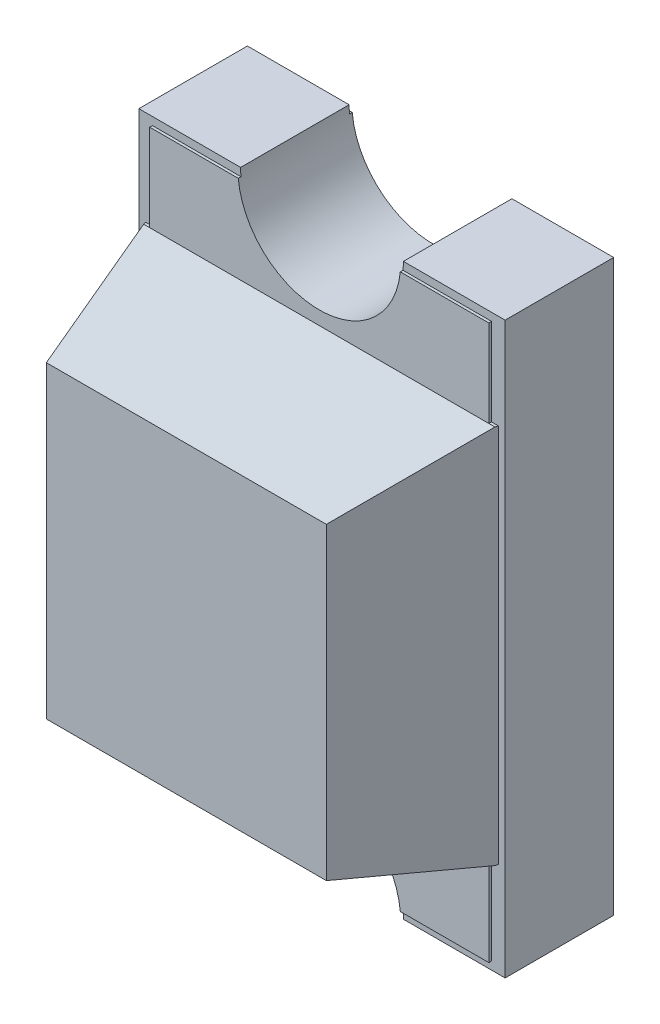
SolidWorks part; units mm, degrees
ref_plane "Front Plane" through (0, 0, 0) normal (0, 0, 1) x (1, 0, 0)
ref_plane "Top Plane" through (0, 0, 0) normal (0, 1, 0) x (1, 0, 0)
ref_plane "Right Plane" through (0, 0, 0) normal (1, 0, 0) x (0, 0, -1)
sketch "Sketch1" plane through (0, 0, 0) normal (0, 0, 1) x (1, 0, 0)
  line L0 (0, 0) -> (0, 842.0202) construction
  line L1 (0, 0) -> (842.0202, 0) construction
  line L3 (-0.675, 1.05) -> (0.675, 1.05)
  line L4 (-0.675, 1.05) -> (-0.675, -1.05)
  line L5 (-0.675, -1.05) -> (0.675, -1.05)
  line L6 (0.675, 1.05) -> (0.675, -1.05)
  dimension "D1" = 1.35
  dimension "D2" = 2.1
extrude "Boss-Extrude1" add sketch "Sketch1" along normal blind 0.4
sketch "Sketch3" plane through (0, 0, 0.4) normal (0, 0, 1) x (1, 0, 0)
  line L0 (0, 0) -> (0, 50000) construction
  line L1 (0, 0) -> (50000, 0) construction
  line L2 (-0.625, 1.0209) -> (0.625, 1.0209)
  line L3 (-0.625, 1.0209) -> (-0.625, 0.5209)
  line L4 (-0.625, 0.5209) -> (0.625, 0.5209)
  line L5 (0.625, 1.0209) -> (0.625, 0.5209)
  line L6 (-0.625, -1.0209) -> (-0.625, -0.5209)
  line L7 (-0.625, -0.5209) -> (0.625, -0.5209)
  line L8 (0.625, -1.0209) -> (0.625, -0.5209)
  line L9 (-0.625, -1.0209) -> (0.625, -1.0209)
  dimension "D1" = 1.25
  dimension "D2" = 0.5
extrude "Boss-Extrude2" add sketch "Sketch3" along normal blind 0.01 and the other way blind 0.41
sketch "Sketch2" plane through (0, 0, 0.4) normal (0, 0, 1) x (1, 0, 0)
  line L0 (0.675, 1.05) -> (-0.675, 1.05) construction
  line L1 (-0.675, -1.05) -> (0.675, -1.05) construction
  circle A0 centre (0, 1.05) radius 0.3
  circle A1 centre (0, -1.05) radius 0.3
  dimension "D1" = 0.6
extrude "Cut-Extrude1" cut sketch "Sketch2" against normal through all both and the other way through all
sketch "Sketch4" plane through (0, 0, 0.4) normal (0, 0, 1) x (1, 0, 0)
  line L0 (0, 0) -> (0, 50000) construction
  line L1 (0, 0) -> (50000, 0) construction
  line L3 (-0.65, 0.7) -> (0.65, 0.7)
  line L4 (-0.65, 0.7) -> (-0.65, -0.7)
  line L5 (-0.65, -0.7) -> (0.65, -0.7)
  line L6 (0.65, 0.7) -> (0.65, -0.7)
  dimension "D1" = 1.4
  dimension "D2" = 1.3
extrude "Boss-Extrude3" add sketch "Sketch4" along normal blind 0.5
sketch "Sketch5" plane through (0, -0.7, 0) normal (0, -1, 0) x (1, 0, 0)
  line L0 (-0.516, 0.9) -> (-0.8627, 0.9)
  line L1 (-0.65, 0.4) -> (-0.516, 0.9)
  line L2 (-0.65, 0.9) -> (0.65, 0.9) construction
  line L3 (-0.8627, 0.9) -> (-0.8627, 0.4)
  line L4 (0, 0) -> (0, 50000) construction
  line L5 (-0.8627, 0.4) -> (-0.65, 0.4)
  line L6 (0.8627, 0.4) -> (0.65, 0.4)
  line L7 (0.8627, 0.9) -> (0.8627, 0.4)
  line L8 (0.516, 0.9) -> (0.8627, 0.9)
  line L9 (0.65, 0.4) -> (0.516, 0.9)
extrude "Cut-Extrude2" cut sketch "Sketch5" against normal through all
sketch "Sketch6" plane through (-0.675, 0, 0) normal (-1, 0, 0) x (0, 0, 1)
  line L0 (0, 0) -> (50000, 0) construction
  line L1 (0.41, -0.7) -> (0.9, -0.7)
  line L2 (0.9, -0.7) -> (0.9, -0.5687)
  line L3 (0.9, -0.7) -> (0.9, 0.7) construction
  line L4 (0.9, -0.5687) -> (0.41, -0.7)
  line L5 (0.9, 0.7) -> (0.9, 0.5687)
  line L6 (0.41, 0.7) -> (0.9, 0.7)
  line L7 (0.9, 0.5687) -> (0.41, 0.7)
  dimension "D1" = 15
extrude "Cut-Extrude3" cut sketch "Sketch6" against normal through all
